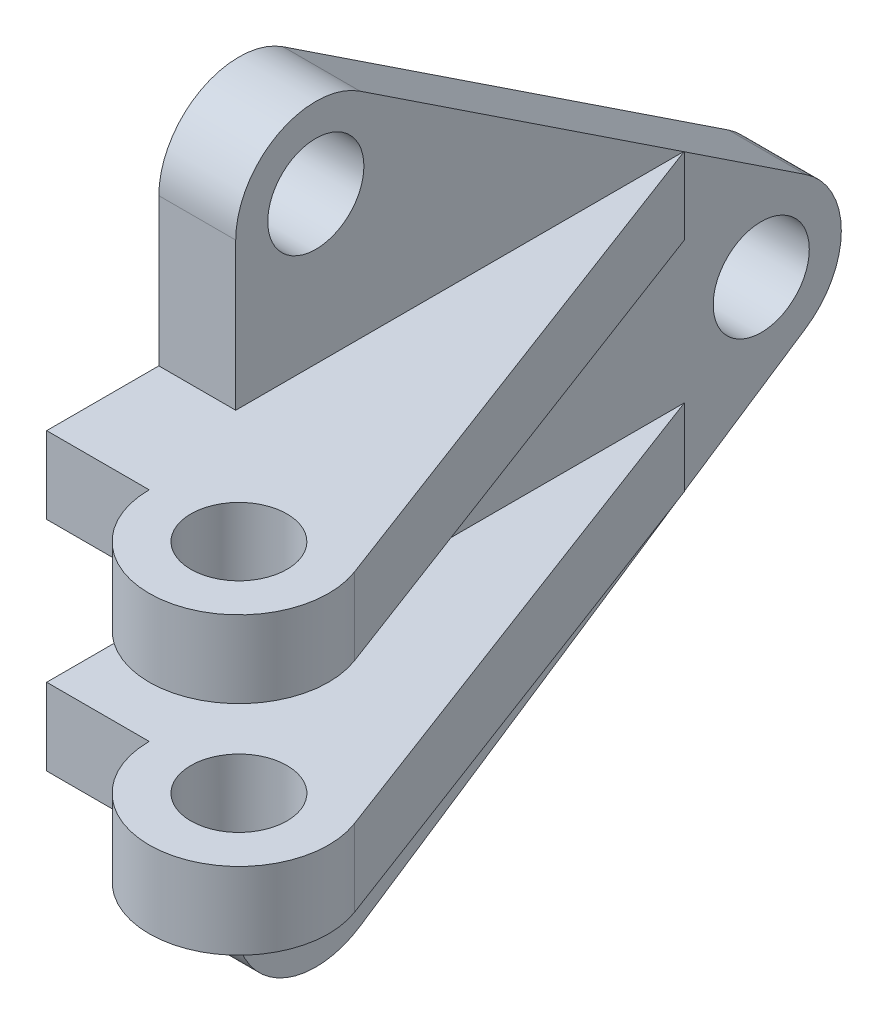
SolidWorks part; units mm, degrees
ref_plane "Front Plane" through (0, 0, 0) normal (1, 0, 0) x (0, 1, 0)
ref_plane "Top Plane" through (0, 0, 0) normal (0, 0, 1) x (0, 1, 0)
ref_plane "Right Plane" through (0, 0, 0) normal (0, 1, 0) x (-1, 0, 0)
sketch "Sketch1" plane through (0, 0, 0) normal (1, 0, 0) x (0, 1, 0)
  line L0 (0, 0) -> (0, 28.9222) construction
  line L1 (-46, 82) -> (46, 82)
  line L2 (-56.4236, 62.6009) -> (-10.4236, -6.8991)
  line L3 (56.4236, 62.6009) -> (10.4236, -6.8991)
  circle A0 centre (0, 0) radius 7.5
  arc A1 (-10.4236, -6.8991) -> (10.4236, -6.8991) centre (0, 0) ccw
  circle A2 centre (46, 69.5) radius 7.5
  arc A3 (56.4236, 62.6009) -> (46, 82) centre (46, 69.5) ccw
  circle A4 centre (-46, 69.5) radius 7.5
  arc A5 (-56.4236, 62.6009) -> (-46, 82) centre (-46, 69.5) cw
  point P8 (46, 82)
  dimension "D1" = 15
  dimension "D2" = 25
  dimension "D3" = 46
  dimension "D4" = 82
extrude "Boss-Extrude1" add sketch "Sketch1" against normal blind 12
sketch "Sketch2" plane through (0, 0, 0) normal (0, 1, 0) x (-1, 0, 0)
  line L0 (12, 62.6009) -> (12, 82) construction
  line L1 (12, 99.5) -> (-4, 99.5)
  line L2 (-31.1013, 94.5649) -> (0, 12)
  line L3 (0, 51.975) -> (0, -51.975) construction
  line L6 (0, -12.5) -> (12, -12.5) construction
  line L7 (12, 99.5) -> (12, 82)
  line L8 (12, 82) -> (0, 82)
  line L9 (0, 82) -> (0, 12)
  arc A0 (-4, 99.5) -> (-31.1013, 94.5649) centre (-18, 99.5) ccw
  circle A1 centre (-18, 99.5) radius 7.5
  dimension "D2" = 14
  dimension "D4" = 15
  dimension "D1" = 70
  dimension "D3" = 16
  dimension "D5" = 112
extrude "Boss-Extrude2" add sketch "Sketch2" against normal mid plane 46
sketch "Sketch3" plane through (0, 0, 99.5) normal (0, 0, 1) x (1, 0, 0)
  line L0 (-12, -23) -> (-12, 23) construction
  line L1 (-12, 11) -> (32, 11)
  line L2 (-12, 11) -> (-12, -11)
  line L3 (-12, -11) -> (32, -11)
  line L4 (32, 11) -> (32, -11)
  line L5 (32, -23) -> (32, 23) construction
  point P8 (-12, 0)
  dimension "D1" = 22
extrude "Cut-Extrude1" cut sketch "Sketch3" against normal up to surface (17.5 mm away) up to face at (-6, -34.5, 82)
sketch "Sketch4" plane through (0, 0, 82) normal (0, 0, 1) x (1, 0, 0)
  line L1 (4, 11) -> (32, 11)
  line L2 (4, 11) -> (4, -11)
  line L3 (4, -11) -> (32, -11)
  line L4 (32, 11) -> (32, -11)
extrude "Cut-Extrude2" cut sketch "Sketch4" against normal through all both and the other way through all
sketch "Sketch5" plane through (0, 0, 82) normal (0, 0, 1) x (1, 0, 0)
  line L0 (4, -11) -> (-12, -11) construction
  line L6 (0, 11) -> (4, 11)
  line L7 (0, 11) -> (0, -11)
  line L8 (0, -11) -> (4, -11)
  line L9 (4, 11) -> (4, -11)
extrude "Cut-Extrude3" cut sketch "Sketch5" against normal through all both and the other way through all
